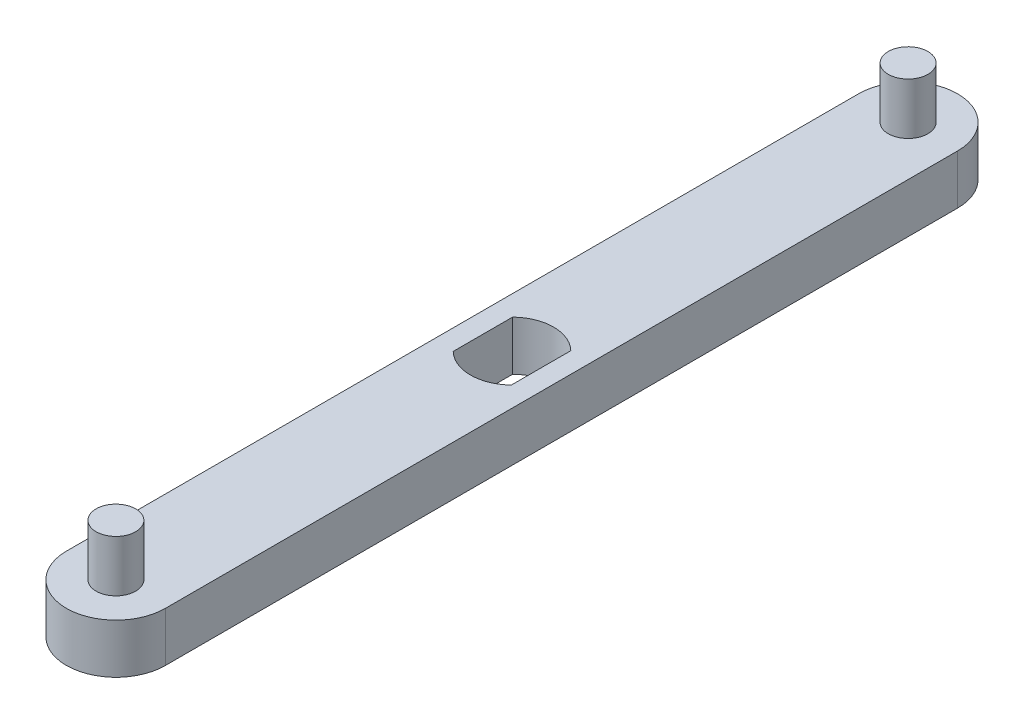
SolidWorks part; units mm, degrees
ref_plane "Front Plane" through (0, 0, 0) normal (0, 0, 1) x (1, 0, 0)
ref_plane "Top Plane" through (0, 0, 0) normal (0, 1, 0) x (1, 0, 0)
ref_plane "Right Plane" through (0, 0, 0) normal (1, 0, 0) x (0, 0, -1)
sketch "Sketch4" plane through (0, 0, 0) normal (0, 1, 0) x (1, 0, 0)
  line L0 (0, 25.4) -> (0, -25.4)
  line L1 (-3.175, 25.4) -> (-3.175, -25.4)
  line L2 (3.175, -25.4) -> (3.175, 25.4)
  arc A0 (-3.175, -25.4) -> (3.175, -25.4) centre (0, -25.4) ccw
  arc A1 (3.175, 25.4) -> (-3.175, 25.4) centre (0, 25.4) ccw
  point P4 (0, 0)
  dimension "D1" = 6.35
  dimension "D2" = 50.8
sketch "Sketch7" plane through (0, 0, 0) normal (0, 1, 0) x (1, 0, 0)
  line L0 (-3.175, 25.4) -> (-3.175, -25.4)
  line L1 (3.175, -25.4) -> (3.175, 25.4)
  arc A0 (-3.175, -25.4) -> (3.175, -25.4) centre (0, -25.4) ccw
  arc A1 (3.175, 25.4) -> (-3.175, 25.4) centre (0, 25.4) ccw
extrude "Boss-Extrude5" add sketch "Sketch7" along normal blind 3.175
sketch "Sketch8" plane through (0, 3.175, 0) normal (0, 1, 0) x (1, 0, 0)
  circle A0 centre (0, 25.4) radius 1.27
  circle A1 centre (0, -25.4) radius 1.27
extrude "Boss-Extrude6" add sketch "Sketch8" along normal blind 3.302
sketch "Sketch9" plane through (0, 0, 0) normal (0, -1, 0) x (1, 0, 0)
  line L2 (-1.8665, 1.905) -> (-1.8665, -1.905)
  line L3 (1.8665, 1.905) -> (1.8665, -1.905)
  arc A2 (-1.8665, -1.905) -> (1.8665, -1.905) centre (0, 0) ccw
  arc A3 (1.8665, 1.905) -> (-1.8665, 1.905) centre (0, 0) ccw
  dimension "D1" = 5.334
  dimension "D2" = 3.81
  dimension "D3" = 3.81
extrude "Cut-Extrude3" cut sketch "Sketch9" against normal through all
